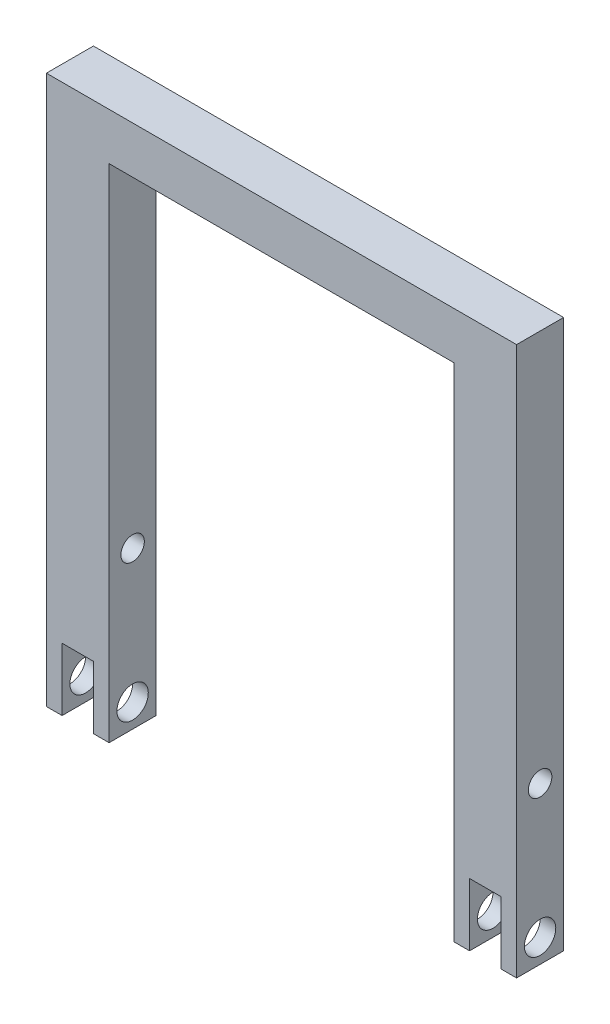
SolidWorks part; units mm, degrees
ref_plane "Front Plane" through (0, 0, 0) normal (0, 0, 1) x (1, 0, 0)
ref_plane "Top Plane" through (0, 0, 0) normal (0, 1, 0) x (1, 0, 0)
ref_plane "Right Plane" through (0, 0, 0) normal (1, 0, 0) x (0, 0, -1)
sketch "Sketch2" plane through (0, 0, 0) normal (0, 0, 1) x (1, 0, 0)
  line L1 (-150, 179.2829) -> (150, 179.2829)
  line L2 (-150, 179.2829) -> (-150, -170.7171)
  line L3 (-150, -170.7171) -> (150, -170.7171)
  line L4 (150, 179.2829) -> (150, -170.7171)
  point P4 (0, 179.2829)
  dimension "D1" = 350
  dimension "D2" = 300
extrude "Boss-Extrude1" add sketch "Sketch2" along normal blind 30
sketch "Sketch3" plane through (0, 0, 30) normal (0, 0, 1) x (1, 0, 0)
  line L0 (-150, 179.2829) -> (-150, -170.7171) construction
  line L1 (-110, 149.2829) -> (110, 149.2829)
  line L2 (-110, 149.2829) -> (-110, -170.7171)
  line L3 (-110, -170.7171) -> (110, -170.7171)
  line L4 (110, 149.2829) -> (110, -170.7171)
  line L5 (150, 179.2829) -> (-150, 179.2829) construction
  line L6 (150, -170.7171) -> (150, 179.2829) construction
  line L7 (-150, -170.7171) -> (150, -170.7171) construction
  dimension "D1" = 40
  dimension "D2" = 30
  dimension "D3" = 40
  dimension "D4" = 0
extrude "Cut-Extrude1" cut sketch "Sketch3" against normal through all
sketch "Sketch4" plane through (-150, 0, 0) normal (-1, 0, 0) x (0, 0, 1)
  line L0 (15, 179.2829) -> (15, -170.7171) construction
  line L1 (30, 179.2829) -> (0, 179.2829) construction
  line L2 (30, -170.7171) -> (0, -170.7171) construction
  circle A0 centre (15, -70.7171) radius 7.5
  circle A1 centre (15, -155.7171) radius 10
  dimension "D1" = 15
  dimension "D3" = 20
  dimension "D4" = 15
  dimension "D2" = 100
extrude "Cut-Extrude2" cut sketch "Sketch4" against normal through all
sketch "Sketch7" plane through (0, -170.7171, 0) normal (0, -1, 0) x (1, 0, 0)
  line L0 (-150, 30) -> (-150, 0) construction
  line L1 (-140, 30) -> (-120, 30)
  line L2 (-140, 30) -> (-140, 0)
  line L3 (-140, 0) -> (-120, 0)
  line L4 (-120, 30) -> (-120, 0)
  line L5 (-110, 0) -> (-110, 30) construction
  line L6 (-150, 0) -> (-110, 0) construction
  line L7 (-150, 30) -> (-110, 30) construction
  point P4 (-140, 15)
  dimension "D1" = 10
  dimension "D2" = 10
  dimension "D3" = 0
  dimension "D4" = 0
extrude "Cut-Extrude3" cut sketch "Sketch7" against normal blind 40
sketch "Sketch8" plane through (0, -170.7171, 0) normal (0, -1, 0) x (1, 0, 0)
  line L0 (110, 30) -> (150, 30) construction
  line L1 (120, 30) -> (140, 30)
  line L2 (120, 30) -> (120, 0)
  line L3 (120, 0) -> (140, 0)
  line L4 (140, 30) -> (140, 0)
  line L5 (110, 0) -> (150, 0) construction
  line L6 (110, 0) -> (110, 30) construction
  line L7 (150, 30) -> (150, 0) construction
  dimension "D1" = 10
  dimension "D2" = 10
extrude "Cut-Extrude4" cut sketch "Sketch8" against normal blind 40
